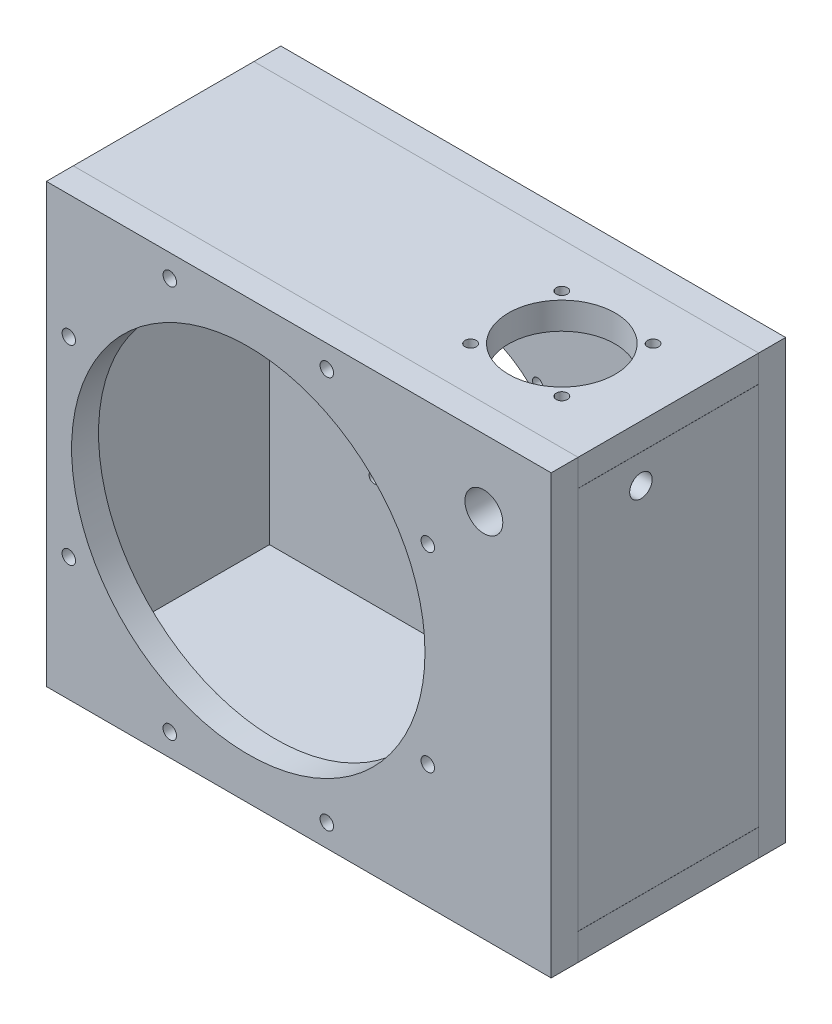
SolidWorks part; units mm, degrees
ref_plane "前视基准面" through (0, 0, 0) normal (0, 0, 1) x (1, 0, 0)
ref_plane "上视基准面" through (0, 0, 0) normal (0, 1, 0) x (1, 0, 0)
ref_plane "右视基准面" through (0, 0, 0) normal (1, 0, 0) x (0, 0, -1)
sketch "草图1" plane through (0, 0, 0) normal (0, 0, 1) x (1, 0, 0)
  line L1 (0, 0) -> (450, 0)
  line L2 (0, 0) -> (0, -390)
  line L3 (0, -390) -> (450, -390)
  line L4 (450, 0) -> (450, -390)
  dimension "D1" = 450
  dimension "D2" = 390
extrude "拉伸1" add sketch "草图1" along normal blind 24
sketch "草图2" plane through (0, 0, 24) normal (0, 0, 1) x (1, 0, 0)
  line L0 (24, -24) -> (24, -366)
  line L1 (0, 0) -> (450, 0)
  line L2 (0, 0) -> (0, -390)
  line L3 (0, -390) -> (450, -390)
  line L4 (450, 0) -> (450, -390)
  line L5 (24, -366) -> (426, -366)
  line L6 (426, -24) -> (426, -366)
  line L7 (24, -24) -> (426, -24)
  dimension "D1" = 24
extrude "拉伸2" add sketch "草图2" along normal blind 161 separate body
sketch "草图3" plane through (0, 0, 185) normal (0, 0, 1) x (1, 0, 0)
  line L1 (0, 0) -> (450, 0)
  line L2 (0, 0) -> (0, -390)
  line L3 (0, -390) -> (450, -390)
  line L4 (450, 0) -> (450, -390)
  dimension "D1" = 390
extrude "拉伸3" add sketch "草图3" along normal blind 24 separate body
sketch "草图4" plane through (0, 0, 209) normal (0, 0, 1) x (1, 0, 0)
  line L0 (0, 0) -> (0, -390) construction
  line L1 (0, -390) -> (450, -390) construction
  circle A0 centre (180, -195) radius 157.5
  dimension "D1" = 180
  dimension "D2" = 315
  dimension "D3" = 195
sketch "草图5" plane through (0, -390, 0) normal (0, -1, 0) x (1, 0, 0)
  line L0 (450, 24) -> (450, 0) construction
  line L1 (0, 209) -> (450, 209) construction
  circle A0 centre (355, 104.5) radius 47.5
  dimension "D2" = 104.5
  dimension "D1" = 95
  dimension "D3" = 95
sketch "草图6" plane through (0, 0, 0) normal (0, 0, -1) x (-1, 0, 0)
  line L0 (0, -390) -> (-450, -390) construction
  line L1 (-450, -390) -> (-450, 0) construction
  circle A0 centre (-180, -195) radius 95
  dimension "D1" = 190
  dimension "D2" = 195
  dimension "D3" = 270
extrude "切除-拉伸3" cut sketch "草图6" against normal blind 33
extrude "切除-拉伸5" cut sketch "草图4" against normal blind 43
extrude "切除-拉伸6" cut sketch "草图5" against normal blind 43
sketch "草图10" plane through (0, -390, 0) normal (0, -1, 0) x (1, 0, 0)
  circle A1 centre (395.6586, 145.1586) radius 5
  circle A2 centre (395.6586, 63.8414) radius 5
  circle A3 centre (314.3414, 63.8414) radius 5
  circle A4 centre (314.3414, 145.1586) radius 5
  dimension "D1" = 10
extrude "切除-拉伸7" cut sketch "草图10" against normal blind 18
sketch "草图11" plane through (0, 0, 0) normal (-1, 0, 0) x (0, 0, 1)
  line L1 (185, 0) -> (185, -390) construction
  line L2 (185, 0) -> (24, 0) construction
  line L3 (185, -24.1) -> (185, -24)
  line L4 (24, -24) -> (185, -24)
  line L6 (24, -24.1) -> (185, -24.1)
  line L7 (24, -24.1) -> (24, -24)
  line L9 (24, -365.9) -> (24, -366)
  line L10 (24, -365.9) -> (185, -365.9)
  line L11 (24, -366) -> (185, -366)
  line L12 (185, -365.9) -> (185, -366)
  line L13 (185, -390) -> (24, -390) construction
  dimension "D1" = 0.1
  dimension "D2" = 24
  dimension "D3" = 0.1
  dimension "D4" = 24
extrude "切除-拉伸8" cut sketch "草图11" against normal through all
sketch "草图12" plane through (0, 0, 0) normal (0, 1, 0) x (1, 0, 0)
  circle A0 centre (355, -104.5) radius 47.5
  dimension "D1" = 95
extrude "切除-拉伸9" cut sketch "草图12" against normal blind 40.2
sketch "草图13" plane through (0, 0, 0) normal (0, 1, 0) x (1, 0, 0)
  circle A0 centre (395.6586, -145.1586) radius 5
  circle A1 centre (314.3414, -145.1586) radius 5
  circle A2 centre (395.6586, -63.8414) radius 5
  circle A3 centre (314.3414, -63.8414) radius 5
extrude "切除-拉伸10" cut sketch "草图13" against normal blind 18
ref_plane "基准面1" through (0, 0, 24) normal (0, 0, -1) x (-1, 0, 0)
sketch "草图14" plane through (0, 0, 24) normal (0, 0, -1) x (-1, 0, 0)
  line L0 (0, -366) -> (-450, -366) construction
  line L1 (-24, -24.1) -> (-14, -24.1)
  line L2 (-24, -24.1) -> (-24, -366)
  line L3 (-24, -366) -> (-14, -366)
  line L4 (-14, -24.1) -> (-14, -366)
  line L5 (0, 0) -> (0, -390) construction
  line L8 (-436, -24.1) -> (-436, -366)
  line L9 (-426, -366) -> (-436, -366)
  line L10 (-426, -24.1) -> (-426, -366)
  line L11 (-426, -24.1) -> (-436, -24.1)
  dimension "D1" = 14
extrude "切除-拉伸12" cut sketch "草图14" against normal blind 161
sketch "草图17" plane through (0, -390, 0) normal (0, -1, 0) x (1, 0, 0)
  line L0 (70, 194.5) -> (200, 194.5) construction
  line L1 (70, 194.5) -> (70, 14.5) construction
  line L2 (0, 0) -> (450, 0) construction
  line L3 (0, 209) -> (450, 209) construction
  line L4 (0, 185) -> (0, 24) construction
  line L5 (0, 209) -> (0, 185) construction
  circle A0 centre (70, 194.5) radius 4
  circle A1 centre (200, 194.5) radius 4
  circle A2 centre (70, 14.5) radius 4
  circle A3 centre (200, 14.5) radius 4
  dimension "D2" = 8
  dimension "D3" = 14.5
  dimension "D4" = 200
  dimension "D5" = 70
  dimension "D6" = 70
  dimension "D7" = 14.5
  dimension "D1" = 90
extrude "切除-拉伸14" cut sketch "草图17" against normal blind 20
sketch "草图19" plane through (0, 0, 0) normal (0, 0, -1) x (-1, 0, 0)
  line L0 (-450, -390) -> (-450, 0) construction
  line L1 (-400, -15) -> (-225, -15) construction
  line L2 (-400, -15) -> (-400, -375) construction
  circle A0 centre (-400, -15) radius 8
  circle A1 centre (-225, -15) radius 8
  circle A2 centre (-50, -15) radius 8
  circle A3 centre (-400, -375) radius 8
  circle A4 centre (-225, -375) radius 8
  circle A5 centre (-50, -375) radius 8
  dimension "D1" = 16
  dimension "D2" = 50
  dimension "D3" = 90
extrude "切除-拉伸18" cut sketch "草图19" against normal blind 20
sketch "草图20" plane through (0, 0, 209) normal (0, 0, 1) x (1, 0, 0)
  circle A0 centre (110, -20) radius 6
  circle A1 centre (250, -20) radius 6
  circle A2 centre (110, -370) radius 6
  circle A3 centre (250, -370) radius 6
  circle A4 centre (20, -110) radius 6
  circle A5 centre (340, -110) radius 6
  circle A6 centre (20, -280) radius 6
  circle A7 centre (340, -280) radius 6
extrude "切除-拉伸19" cut sketch "草图20" against normal blind 20
sketch "草图21" plane through (450, 0, 0) normal (1, 0, 0) x (0, 0, -1)
  line L0 (-209, -390) -> (-209, 0) construction
  circle A0 centre (-129, -50) radius 10
  dimension "D1" = 80
extrude "切除-拉伸20" cut sketch "草图21" against normal blind 35
sketch "草图22" plane through (0, 0, 209) normal (0, 0, 1) x (1, 0, 0)
  line L0 (450, -390) -> (450, 0) construction
  line L1 (450, 0) -> (0, 0) construction
  circle A0 centre (390, -60) radius 16.875
  dimension "D1" = 60
  dimension "D2" = 60
  dimension "D3" = 33.75
extrude "切除-拉伸21" cut sketch "草图22" against normal blind 40
sketch "草图23" plane through (0, 0, 0) normal (0, 0, -1) x (-1, 0, 0)
  circle A0 centre (-180, -195) radius 103
  circle A1 centre (-283, -195) radius 4.5
  dimension "D1" = 206
  dimension "D2" = 9
extrude "切除-拉伸22" cut sketch "草图23" against normal through all contours A1
pattern_circular "阵列(圆周)1" count 16 over 360 about axis through (180, -195, 0) along (0, 0, 1) of "切除-拉伸22"
